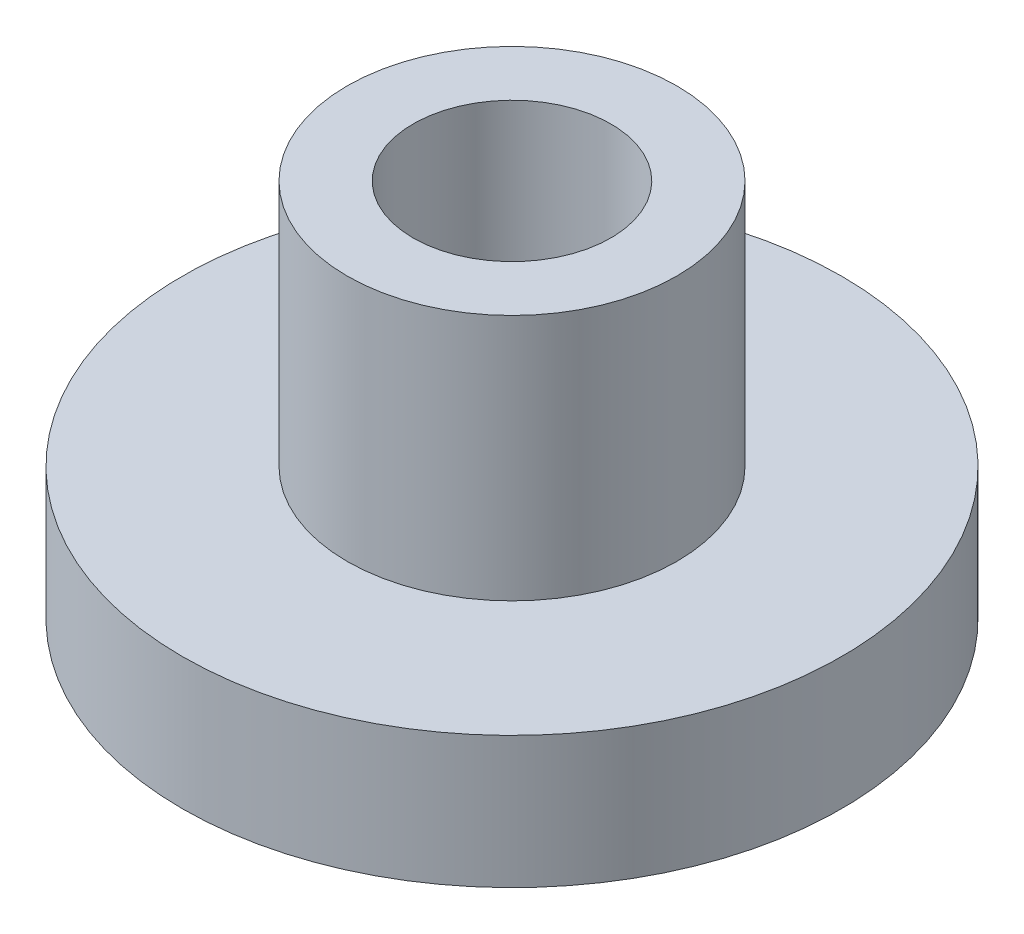
SolidWorks part; units mm, degrees
ref_plane "Front Plane" through (0, 0, 0) normal (0, 0, 1) x (1, 0, 0)
ref_plane "Top Plane" through (0, 0, 0) normal (0, 1, 0) x (1, 0, 0)
ref_plane "Right Plane" through (0, 0, 0) normal (1, 0, 0) x (0, 0, -1)
sketch "Sketch1" plane through (0, 0, 0) normal (0, 1, 0) x (1, 0, 0)
  circle A0 centre (0, 0) radius 5
  dimension "D1" = 10
extrude "Boss-Extrude1" add sketch "Sketch1" along normal blind 2 contours A0
sketch "Sketch2" plane through (0, 2, 0) normal (0, 1, 0) x (1, 0, 0)
  circle A0 centre (0, 0) radius 2.5
  dimension "D1" = 5
extrude "Boss-Extrude2" add sketch "Sketch2" along normal blind 3.75
sketch "Sketch3" plane through (0, 5.75, 0) normal (0, 1, 0) x (1, 0, 0)
  circle A0 centre (0, 0) radius 1.5
  dimension "D1" = 3
extrude "Cut-Extrude1" cut sketch "Sketch3" against normal blind 4
